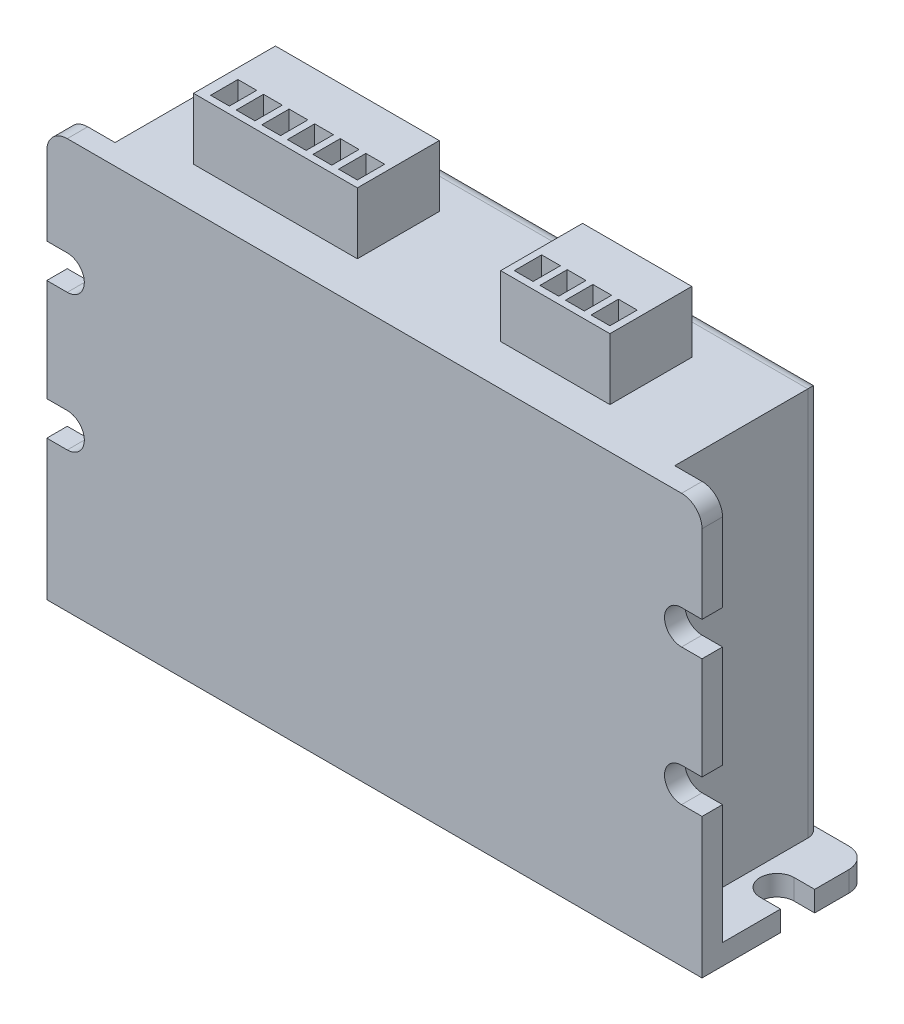
SolidWorks part; units mm, degrees
ref_plane "Front Plane" through (0, 0, 0) normal (0, 0, 1) x (1, 0, 0)
ref_plane "Top Plane" through (0, 0, 0) normal (0, 1, 0) x (1, 0, 0)
ref_plane "Right Plane" through (0, 0, 0) normal (1, 0, 0) x (0, 0, -1)
sketch "Sketch1" plane through (0, 0, 0) normal (0, 1, 0) x (1, 0, 0)
  line L1 (0, 0) -> (96, 0)
  line L2 (0, 0) -> (0, 24.5)
  line L3 (0, 24.5) -> (96, 24.5)
  line L4 (96, 0) -> (96, 24.5)
  dimension "D1" = 24.5
  dimension "D2" = 96
extrude "Boss-Extrude1" add sketch "Sketch1" along normal blind 3
sketch "Sketch2" plane through (0, 3, 0) normal (0, 1, 0) x (1, 0, 0)
  line L0 (96, 0) -> (96, 24.5) construction
  line L1 (0, 0) -> (96, 0)
  line L2 (0, 0) -> (0, 3)
  line L3 (0, 3) -> (7, 3)
  line L4 (96, 0) -> (96, 3)
  line L5 (96, 24.5) -> (0, 24.5) construction
  line L7 (7, 3) -> (7, 24.5)
  line L8 (7, 24.5) -> (89, 24.5)
  line L9 (89, 3) -> (89, 24.5)
  line L10 (96, 24.5) -> (0, 24.5) construction
  line L11 (89, 3) -> (96, 3)
  point P13 (48, 24.5)
  point P16 (48, 24.5)
  dimension "D1" = 3
  dimension "D2" = 82
extrude "Boss-Extrude2" add sketch "Sketch2" along normal blind 57
fillet "Fillet1" radius 2 3 edges at (7, 31.5, -24.5) (89, 31.5, -24.5) (48, 60, -24.5)
fillet "Fillet2" radius 3 4 edges at (0, 1.5, -24.5) (96, 1.5, -24.5) (0, 60, -1.5) (96, 60, -1.5)
sketch "Sketch3" plane through (0, 0, -3) normal (0, 0, -1) x (-1, 0, 0)
  line L0 (-93, 45.5) -> (-96, 45.5)
  line L1 (-96, 57) -> (-96, 3) construction
  line L2 (-96, 45.5) -> (-96, 40.5)
  line L3 (-96, 40.5) -> (-93, 40.5)
  line L4 (-93, 25.5) -> (-96, 25.5)
  line L5 (-96, 25.5) -> (-96, 20.5)
  line L6 (-96, 20.5) -> (-93, 20.5)
  line L7 (-3, 25.5) -> (0, 25.5)
  line L8 (0, 57) -> (0, 3) construction
  line L9 (0, 25.5) -> (0, 20.5)
  line L10 (0, 20.5) -> (-3, 20.5)
  line L11 (-3, 45.5) -> (0, 45.5)
  line L12 (0, 45.5) -> (0, 40.5)
  line L13 (0, 40.5) -> (-3, 40.5)
  line L15 (0, 0) -> (-96, 0) construction
  arc A0 (-93, 40.5) -> (-93, 45.5) centre (-93, 43) ccw
  arc A1 (-93, 20.5) -> (-93, 25.5) centre (-93, 23) ccw
  arc A2 (-3, 25.5) -> (-3, 20.5) centre (-3, 23) ccw
  arc A3 (-3, 45.5) -> (-3, 40.5) centre (-3, 43) ccw
  point P1 (0, 0)
  point P3 (0, 0)
  dimension "D1" = 2.5
  dimension "D2" = 3
  dimension "D3" = 23
  dimension "D4" = 20
extrude "Cut-Extrude1" cut sketch "Sketch3" against normal up to next
sketch "Sketch4" plane through (0, 3, 0) normal (0, 1, 0) x (1, 0, 0)
  line L0 (3, 16.5) -> (0, 16.5)
  line L1 (0, 21.5) -> (0, 3) construction
  line L2 (0, 16.5) -> (0, 11.5)
  line L3 (0, 11.5) -> (3, 11.5)
  line L4 (93, 11.5) -> (96, 11.5)
  line L5 (96, 3) -> (96, 21.5) construction
  line L6 (96, 11.5) -> (96, 16.5)
  line L7 (96, 16.5) -> (93, 16.5)
  line L8 (0, 0) -> (96, 0) construction
  arc A0 (93, 16.5) -> (93, 11.5) centre (93, 14) ccw
  arc A1 (3, 11.5) -> (3, 16.5) centre (3, 14) ccw
  point P14 (0, 0)
  dimension "D1" = 2.5
  dimension "D2" = 3
  dimension "D3" = 14
extrude "Cut-Extrude2" cut sketch "Sketch4" against normal up to next
sketch "Sketch5" plane through (0, 60, 0) normal (0, 1, 0) x (1, 0, 0)
  line L0 (89, 3) -> (89, 22.5) construction
  line L1 (76.5, 6) -> (60.5, 6)
  line L2 (76.5, 6) -> (76.5, 18)
  line L3 (76.5, 18) -> (60.5, 18)
  line L4 (60.5, 6) -> (60.5, 18)
  line L5 (39.5, 6) -> (15.5, 6)
  line L6 (39.5, 6) -> (39.5, 18)
  line L7 (39.5, 18) -> (15.5, 18)
  line L8 (15.5, 6) -> (15.5, 18)
  line L9 (7, 22.5) -> (7, 3) construction
  line L10 (3, 0) -> (93, 0) construction
  dimension "D1" = 16
  dimension "D2" = 24
  dimension "D3" = 12
  dimension "D4" = 12.5
  dimension "D5" = 8.5
  dimension "D6" = 6
extrude "Boss-Extrude3" add sketch "Sketch5" along normal blind 9
sketch "Sketch6" plane through (0, 69, 0) normal (0, 1, 0) x (1, 0, 0)
  line L0 (76.5, 6) -> (76.5, 18) construction
  line L1 (75.5, 7) -> (72.75, 7)
  line L2 (75.5, 7) -> (75.5, 11)
  line L3 (75.5, 11) -> (72.75, 11)
  line L4 (72.75, 7) -> (72.75, 11)
  line L5 (60.5, 6) -> (76.5, 6) construction
  dimension "D1" = 1
  dimension "D2" = 1
  dimension "D3" = 2.75
  dimension "D4" = 4
extrude "Cut-Extrude3" cut sketch "Sketch6" against normal blind 6
pattern_linear "LPattern1" count 4 spacing 3.75 along (-1, 0, 0) of "Cut-Extrude3"
sketch "Sketch7" plane through (0, 69, 0) normal (0, 1, 0) x (1, 0, 0)
  line L0 (39.5, 6) -> (39.5, 18) construction
  line L1 (38.5, 7) -> (35.75, 7)
  line L2 (38.5, 7) -> (38.5, 11)
  line L3 (38.5, 11) -> (35.75, 11)
  line L4 (35.75, 7) -> (35.75, 11)
  line L5 (15.5, 6) -> (39.5, 6) construction
  dimension "D1" = 2.75
  dimension "D2" = 1
  dimension "D3" = 1
  dimension "D4" = 4
extrude "Cut-Extrude4" cut sketch "Sketch7" against normal blind 6
pattern_linear "LPattern2" count 6 spacing 3.75 along (-1, 0, 0) of "Cut-Extrude4"
